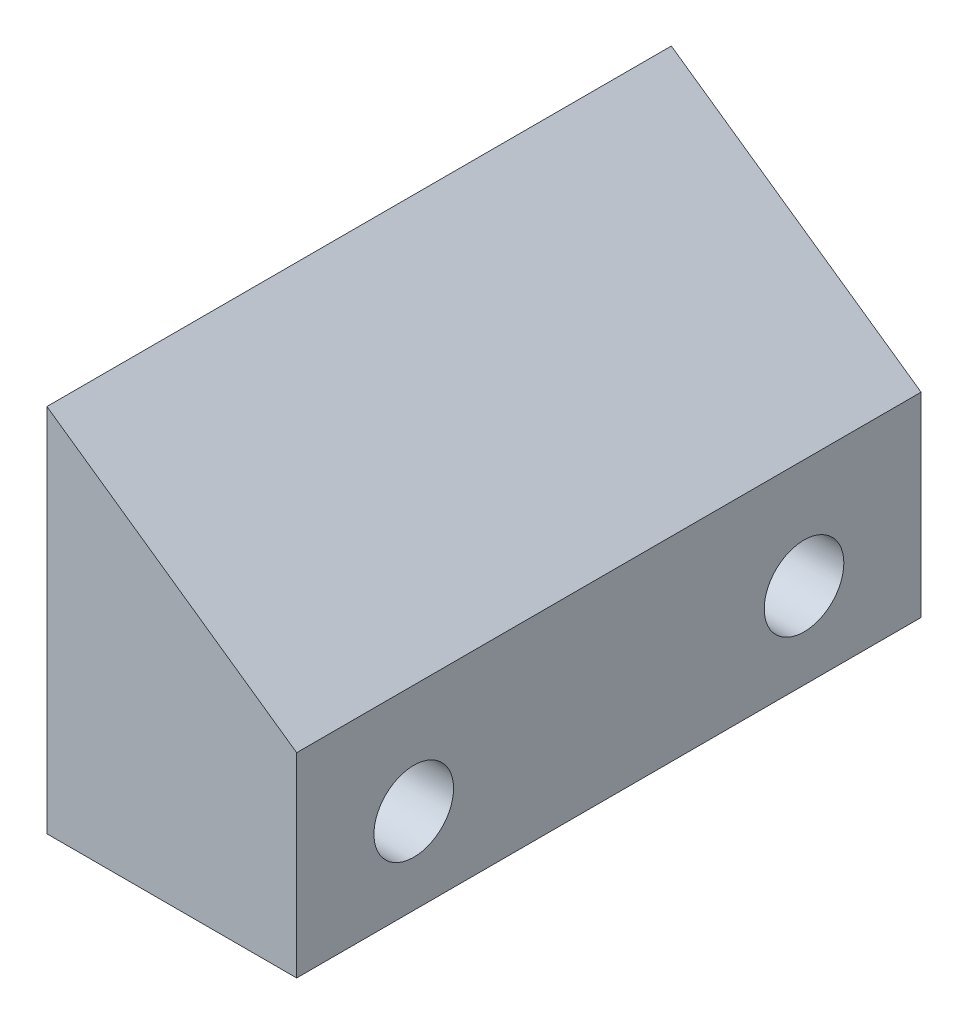
SolidWorks part; units mm, degrees
ref_plane "前视基准面" through (0, 0, 0) normal (0, 0, 1) x (1, 0, 0)
ref_plane "上视基准面" through (0, 0, 0) normal (0, 1, 0) x (1, 0, 0)
ref_plane "右视基准面" through (0, 0, 0) normal (1, 0, 0) x (0, 0, -1)
sketch "草图1" plane through (0, 0, 0) normal (0, 0, 1) x (1, 0, 0)
  line L0 (0, 0) -> (0, 47.4066)
  line L1 (0, -55) -> (0, 55) construction
  line L2 (0, 47.4066) -> (32, 25)
  line L3 (32, 25) -> (32, 0)
  line L4 (55, 0) -> (-55, 0) construction
  line L5 (32, 0) -> (0, 0)
  dimension "D1" = 25
  dimension "D2" = 32
  dimension "D3" = 55
extrude "凸台-拉伸1" add sketch "草图1" along normal mid plane 80
sketch "草图2" plane through (32, 0, 0) normal (1, 0, 0) x (0, 0, -1)
  line L0 (-25, 11) -> (25, 11) construction
  line L2 (0, 17.6) -> (0, -17.6) construction
  line L3 (17.6, 0) -> (-17.6, 0) construction
  point P0 (0, 0)
  point P3 (0, 11)
  dimension "D1" = 50
  dimension "D2" = 11
hole_wizard "M12 螺纹孔1" positions "草图3" profile "草图4" tap size "M12" standard "GB" end condition up to next
sketch "草图3" plane through (32, 0, 0) normal (1, 0, 0) x (0, 0, -1)
  line L0 (-25, 11) -> (25, 11) construction
  point P0 (-25, 11)
  point P3 (25, 11)
sketch "草图4" plane through (32, 11, 25) normal (0, 1, 0) x (0, 0, -1)
  line L0 (0, 0) -> (0, 32)
  line L1 (0, 32) -> (5.1, 32)
  line L2 (5.1, 32) -> (5.1, 0)
  line L5 (5.1, 0) -> (0, 0)
  line L11 (0, -6.35) -> (0, 107.95) construction
  dimension "通孔螺纹孔钻头直径" = 10.2
  dimension "通孔螺纹孔钻头深度" = 32
cosmetic thread "孔螺纹线1"
cosmetic thread "孔螺纹线2"
